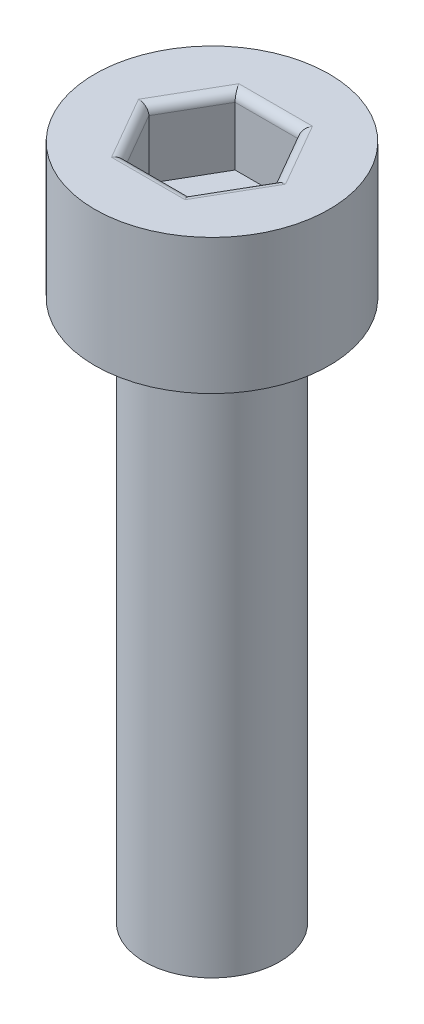
SolidWorks part; units mm, degrees
material "灰铸铁"
ref_plane "前视基准面" through (0, 0, 0) normal (0, 0, 1) x (1, 0, 0)
ref_plane "上视基准面" through (0, 0, 0) normal (0, 1, 0) x (1, 0, 0)
ref_plane "右视基准面" through (0, 0, 0) normal (1, 0, 0) x (0, 0, -1)
other "Configuration Table"
sketch "草图1" plane through (0, 0, 0) normal (0, 1, 0) x (1, 0, 0)
  circle A0 centre (0, 0) radius 2.6
  dimension "D1" = 5.2
extrude "凸台-拉伸1" add sketch "草图1" along normal blind 3
sketch "草图2" plane through (0, 3, 0) normal (0, 1, 0) x (1, 0, 0)
  line L0 (-0.7, 1.2124) -> (0.7, 1.2124)
  line L1 (0.7, 1.2124) -> (1.4, 0)
  line L2 (1.4, 0) -> (0.7, -1.2124)
  line L3 (0.7, -1.2124) -> (-0.7, -1.2124)
  line L4 (-0.7, -1.2124) -> (-1.4, 0)
  line L5 (-1.4, 0) -> (-0.7, 1.2124)
  line L6 (-0.7, 1.2124) -> (0.7, -1.2124) construction
  line L7 (-0.7, -1.2124) -> (0.7, 1.2124) construction
  point P2 (0, 0)
  dimension "D1" = 120
  dimension "D2" = 120
  dimension "D3" = 2.8
  dimension "D4" = 2.8
extrude "切除-拉伸1" cut sketch "草图2" against normal blind 1.5 contours L5 L0 L1 L2 L3 L4
sketch "草图5" plane through (0, 0, 0) normal (0, -1, 0) x (1, 0, 0)
  circle A0 centre (0, 0) radius 1.5
  dimension "D1" = 3
extrude "凸台-拉伸2" add sketch "草图5" along normal blind 12
fillet "圆角1" radius 0.2 6 edges at (0, 3, -1.2124) (-1.05, 3, -0.6062) (-1.05, 3, 0.6062) (1.05, 3, -0.6062) (0, 3, 1.2124) (1.05, 3, 0.6062)
